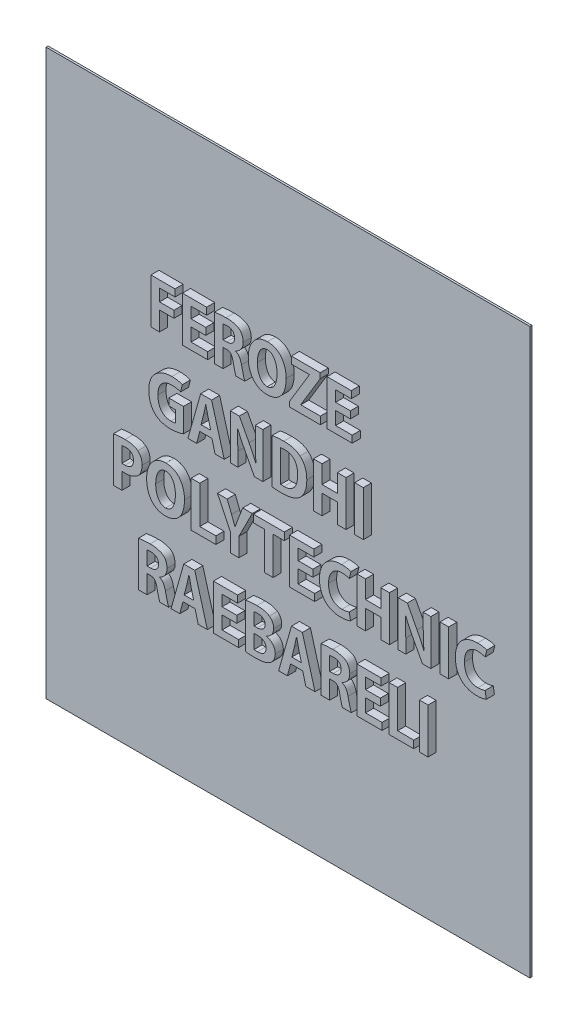
SolidWorks part; units mm, degrees
ref_plane "Front Plane" through (0, 0, 0) normal (0, 0, 1) x (1, 0, 0)
ref_plane "Top Plane" through (0, 0, 0) normal (0, 1, 0) x (1, 0, 0)
ref_plane "Right Plane" through (0, 0, 0) normal (1, 0, 0) x (0, 0, -1)
sketch "Sketch1" plane through (0, 0, 0) normal (0, 0, 1) x (1, 0, 0)
  line L1 (0, 0) -> (120, 0)
  line L2 (0, 0) -> (0, 140)
  line L3 (0, 140) -> (120, 140)
  line L4 (120, 0) -> (120, 140)
  dimension "D1" = 140
  dimension "D2" = 120
extrude "Boss-Extrude1" add sketch "Sketch1" along normal blind 0.5
sketch "Sketch2" plane through (0, 0, 0.5) normal (0, 0, 1) x (1, 0, 0)
  text T0 "   FEROZE \r\n   GANDHI \r\nPOLYTECHNIC\r\n  RAEBARELI" font "Adobe Gothic Std B" height in points 36
extrude "Boss-Extrude2" add sketch "Sketch2" along normal blind 2
